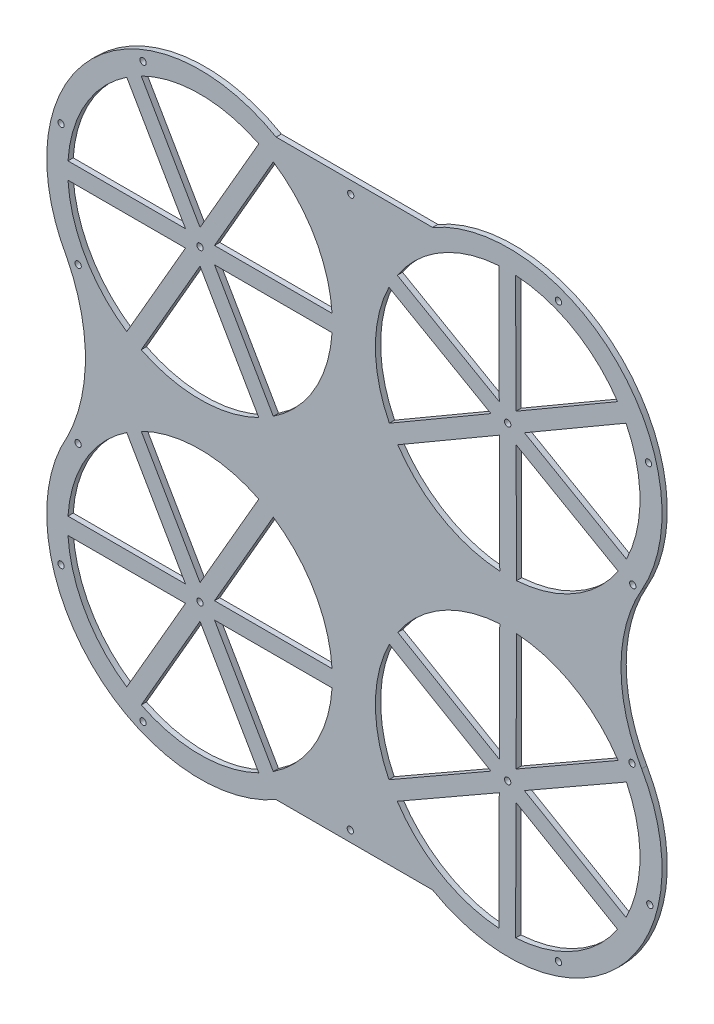
SolidWorks part; units mm, degrees
ref_plane "前视基准面" through (0, 0, 0) normal (0, 0, 1) x (1, 0, 0)
ref_plane "上视基准面" through (0, 0, 0) normal (0, 1, 0) x (1, 0, 0)
ref_plane "右视基准面" through (0, 0, 0) normal (1, 0, 0) x (0, 0, -1)
sketch "Model" plane through (0, 0, 0) normal (0, 0, 1) x (1, 0, 0)
  line L0 (1801.0467, 3384.6259) -> (1652.0535, 3384.6259)
  line L1 (1801.0467, 2838.1756) -> (1652.0535, 2838.1756)
  line L2 (1523.5803, 3370.7873) -> (1579.5501, 3273.8448)
  line L3 (1509.7723, 3362.8153) -> (1565.7421, 3265.8728)
  line L4 (1579.5501, 3241.9566) -> (1635.5199, 3145.0141)
  line L5 (1593.3581, 3249.9287) -> (1649.3278, 3152.9862)
  line L6 (1453.8025, 3265.8728) -> (1565.7421, 3265.8728)
  line L7 (1453.8025, 3249.9287) -> (1565.7421, 3249.9287)
  line L8 (1649.3278, 3362.8153) -> (1593.3581, 3265.8728)
  line L9 (1579.5501, 3241.9566) -> (1523.5803, 3145.0141)
  line L10 (1635.5199, 3370.7873) -> (1579.5501, 3273.8448)
  line L11 (1565.7421, 3249.9287) -> (1509.7723, 3152.9862)
  line L12 (1705.2976, 3265.8728) -> (1593.3581, 3265.8728)
  line L13 (1705.2976, 3249.9287) -> (1593.3581, 3249.9287)
  line L14 (1509.7723, 2859.9862) -> (1565.7421, 2956.9287)
  line L15 (1579.5501, 2980.8448) -> (1635.5199, 3077.7873)
  line L16 (1523.5803, 2852.0141) -> (1579.5501, 2948.9566)
  line L17 (1593.3581, 2972.8728) -> (1649.3278, 3069.8153)
  line L18 (1453.8025, 2956.9287) -> (1565.7421, 2956.9287)
  line L19 (1453.8025, 2972.8728) -> (1565.7421, 2972.8728)
  line L20 (1649.3278, 2859.9862) -> (1593.3581, 2956.9287)
  line L21 (1579.5501, 2980.8448) -> (1523.5803, 3077.7873)
  line L22 (1635.5199, 2852.0141) -> (1579.5501, 2948.9566)
  line L23 (1565.7421, 2972.8728) -> (1509.7723, 3069.8153)
  line L24 (1705.2976, 2956.9287) -> (1593.3581, 2956.9287)
  line L25 (1705.2976, 2972.8728) -> (1593.3581, 2972.8728)
  line L26 (1977.2246, 2893.7676) -> (1880.4734, 2950.0674)
  line L27 (1856.6044, 2963.9568) -> (1759.8531, 3020.2565)
  line L28 (1985.2436, 2907.5484) -> (1888.4924, 2963.8481)
  line L29 (1864.6234, 2977.7375) -> (1767.8722, 3034.0373)
  line L30 (1880.092, 2838.1285) -> (1880.4734, 2950.0674)
  line L31 (1864.148, 2838.1828) -> (1864.5294, 2950.1217)
  line L32 (1977.7001, 3033.3223) -> (1880.5674, 2977.6832)
  line L33 (1856.6044, 2963.9568) -> (1759.4718, 2908.3176)
  line L34 (1985.625, 3019.4873) -> (1888.4924, 2963.8481)
  line L35 (1864.5294, 2950.1217) -> (1767.3967, 2894.4825)
  line L36 (1880.9488, 3089.6221) -> (1880.5674, 2977.6832)
  line L37 (1865.0048, 3089.6764) -> (1864.6234, 2977.7375)
  line L38 (1977.2246, 3329.0338) -> (1880.4734, 3272.7341)
  line L39 (1856.6044, 3258.8447) -> (1759.8531, 3202.545)
  line L40 (1985.2436, 3315.2531) -> (1888.4924, 3258.9533)
  line L41 (1864.6234, 3245.064) -> (1767.8722, 3188.7642)
  line L42 (1880.092, 3384.673) -> (1880.4734, 3272.7341)
  line L43 (1864.148, 3384.6187) -> (1864.5294, 3272.6798)
  line L44 (1977.7001, 3189.4791) -> (1880.5674, 3245.1183)
  line L45 (1856.6044, 3258.8447) -> (1759.4718, 3314.4839)
  line L46 (1985.625, 3203.3142) -> (1888.4924, 3258.9533)
  line L47 (1864.5294, 3272.6798) -> (1767.3967, 3328.3189)
  line L48 (1880.9488, 3133.1794) -> (1880.5674, 3245.1183)
  line L49 (1865.0048, 3133.125) -> (1864.6234, 3245.064)
  arc A0 (1509.7723, 3362.8153) -> (1453.8025, 3265.8728) centre (1579.5501, 3257.9007) ccw
  arc A1 (1652.0535, 3384.6259) -> (1452.9668, 3185.1499) centre (1579.5501, 3257.9007) ccw
  arc A2 (1452.9668, 3037.6516) -> (1652.0535, 2838.1756) centre (1579.5501, 2964.9007) ccw
  arc A3 (2000.1333, 3185.1499) -> (1801.0467, 3384.6259) centre (1873.5501, 3257.9007) ccw
  arc A4 (1801.0467, 2838.1756) -> (2000.1333, 3037.6516) centre (1873.5501, 2964.9007) ccw
  arc A5 (1452.9668, 3037.6516) -> (1452.9668, 3185.1499) centre (1305.7668, 3111.4007) ccw
  arc A6 (2000.1333, 3185.1499) -> (2000.1333, 3037.6516) centre (2128.4535, 3111.4007) ccw
  circle A7 centre (1463.4625, 3185.1499) radius 3
  circle A8 centre (1447.2084, 3293.3223) radius 3
  circle A9 centre (1525.3242, 3383.7123) radius 3
  circle A10 centre (1463.4625, 3037.6516) radius 3
  circle A11 centre (1447.2084, 2929.4791) radius 3
  circle A12 centre (1525.3242, 2839.0892) radius 3
  circle A13 centre (1991.692, 3185.1499) radius 3
  circle A14 centre (2006.6221, 3293.3223) radius 3
  circle A15 centre (1920.8998, 3383.7123) radius 3
  circle A16 centre (1990.9925, 3037.6516) radius 3
  circle A17 centre (2007.9298, 2929.4791) radius 3
  circle A18 centre (1920.8998, 2839.0892) radius 3
  circle A19 centre (1723.112, 3372.8968) radius 3
  circle A20 centre (1722.6695, 2848.468) radius 3
  circle A21 centre (1579.5501, 3257.9007) radius 3
  arc A22 (1453.8025, 3249.9287) -> (1509.7723, 3152.9862) centre (1579.5501, 3257.9007) ccw
  arc A23 (1523.5803, 3145.0141) -> (1635.5199, 3145.0141) centre (1579.5501, 3257.9007) ccw
  arc A24 (1649.3278, 3152.9862) -> (1705.2976, 3249.9287) centre (1579.5501, 3257.9007) ccw
  arc A25 (1705.2976, 3265.8728) -> (1649.3278, 3362.8153) centre (1579.5501, 3257.9007) ccw
  arc A26 (1635.5199, 3370.7873) -> (1523.5803, 3370.7873) centre (1579.5501, 3257.9007) ccw
  arc A27 (1453.8025, 2956.9287) -> (1509.7723, 2859.9862) centre (1579.5501, 2964.9007) ccw
  arc A28 (1509.7723, 3069.8153) -> (1453.8025, 2972.8728) centre (1579.5501, 2964.9007) ccw
  arc A29 (1635.5199, 3077.7873) -> (1523.5803, 3077.7873) centre (1579.5501, 2964.9007) ccw
  arc A30 (1705.2976, 2972.8728) -> (1649.3278, 3069.8153) centre (1579.5501, 2964.9007) ccw
  arc A31 (1649.3278, 2859.9862) -> (1705.2976, 2956.9287) centre (1579.5501, 2964.9007) ccw
  arc A32 (1523.5803, 2852.0141) -> (1635.5199, 2852.0141) centre (1579.5501, 2964.9007) ccw
  circle A33 centre (1579.5501, 2964.9007) radius 3
  arc A34 (1880.092, 2838.1285) -> (1977.2246, 2893.7676) centre (1872.5484, 2963.9024) ccw
  arc A35 (1767.3967, 2894.4825) -> (1864.148, 2838.1828) centre (1872.5484, 2963.9024) ccw
  arc A36 (1759.8531, 3020.2565) -> (1759.4718, 2908.3176) centre (1872.5484, 2963.9024) ccw
  arc A37 (1865.0048, 3089.6764) -> (1767.8722, 3034.0373) centre (1872.5484, 2963.9024) ccw
  arc A38 (1977.7001, 3033.3223) -> (1880.9488, 3089.6221) centre (1872.5484, 2963.9024) ccw
  arc A39 (1985.2436, 2907.5484) -> (1985.625, 3019.4873) centre (1872.5484, 2963.9024) ccw
  circle A40 centre (1872.5484, 2963.9024) radius 3
  arc A41 (1977.2246, 3329.0338) -> (1880.092, 3384.673) centre (1872.5484, 3258.899) ccw
  arc A42 (1864.148, 3384.6187) -> (1767.3967, 3328.3189) centre (1872.5484, 3258.899) ccw
  arc A43 (1759.4718, 3314.4839) -> (1759.8531, 3202.545) centre (1872.5484, 3258.899) ccw
  arc A44 (1767.8722, 3188.7642) -> (1865.0048, 3133.125) centre (1872.5484, 3258.899) ccw
  arc A45 (1880.9488, 3133.1794) -> (1977.7001, 3189.4791) centre (1872.5484, 3258.899) ccw
  arc A46 (1985.625, 3203.3142) -> (1985.2436, 3315.2531) centre (1872.5484, 3258.899) ccw
  circle A47 centre (1872.5484, 3258.899) radius 3
extrude "凸台-拉伸1" add sketch "Model" along normal blind 5
